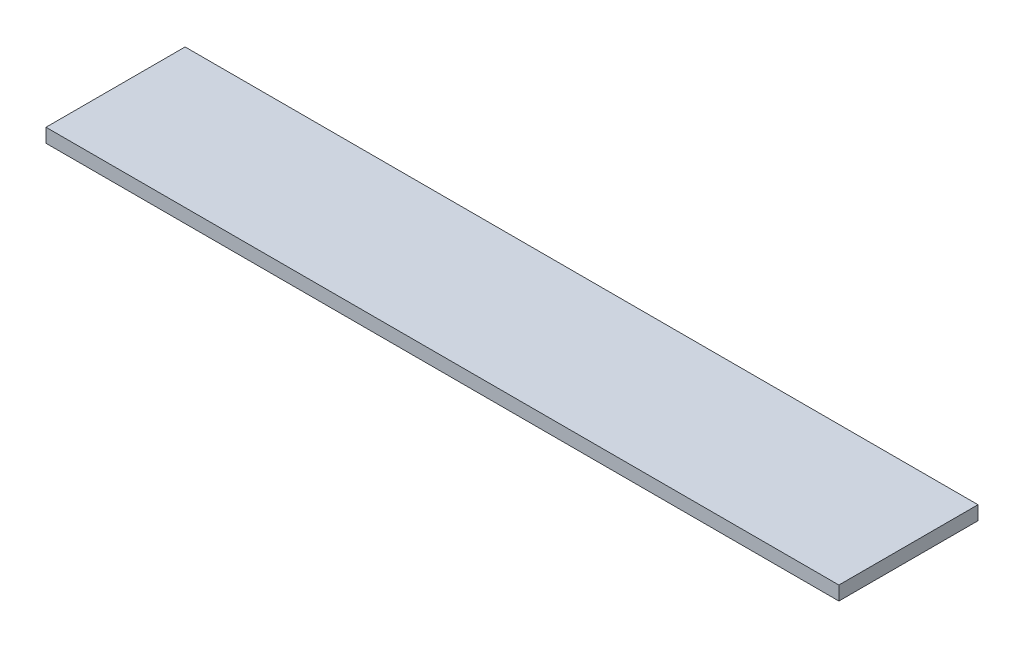
SolidWorks part; units mm, degrees
ref_plane "Front Plane" through (0, 0, 0) normal (0, 0, 1) x (1, 0, 0)
ref_plane "Top Plane" through (0, 0, 0) normal (0, 1, 0) x (1, 0, 0)
ref_plane "Right Plane" through (0, 0, 0) normal (1, 0, 0) x (0, 0, -1)
sketch "Sketch1" plane through (0, 0, 0) normal (0, 0, 1) x (1, 0, 0)
  line L1 (-44.3111, 20.1056) -> (12.6889, 20.1056)
  line L2 (-44.3111, 20.1056) -> (-44.3111, 10.1056)
  line L3 (-44.3111, 10.1056) -> (12.6889, 10.1056)
  line L4 (12.6889, 20.1056) -> (12.6889, 10.1056)
  line L5 (-15.8111, 10.1056) -> (-15.8111, 20.1056) construction
  line L6 (-44.3111, 15.1056) -> (12.6889, 15.1056) construction
  point P104 (-15.8111, 15.1056)
  dimension "D1" = 10
  dimension "D2" = 57
extrude "Boss-Extrude1" add sketch "Sketch1" along normal blind 1
move or copy body "Body-Move/Copy1" bodies to move or copy 102 copy no rotation origin (0, 15.1056, 0.25) rotation axis (1, 0, 0) rotation angle 90
